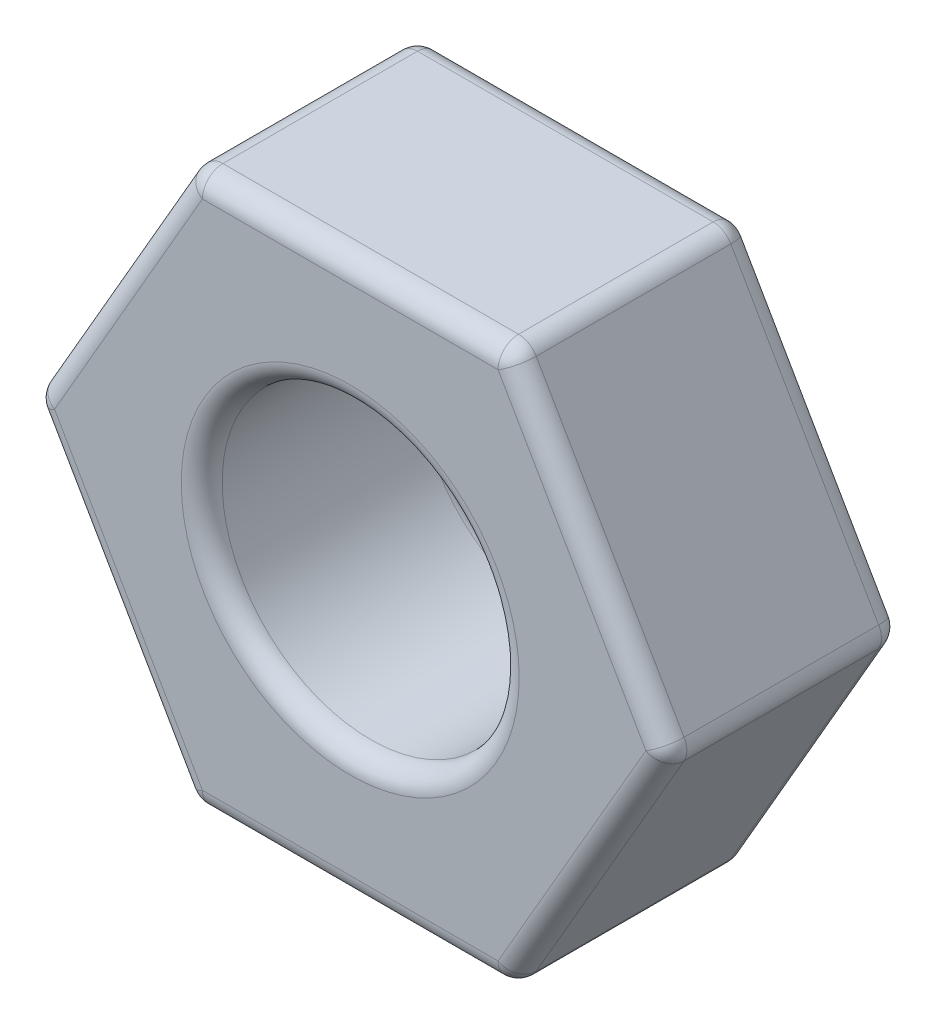
SolidWorks part; units mm, degrees
ref_plane "Plano frontal" through (0, 0, 0) normal (0, 0, 1) x (1, 0, 0)
ref_plane "Plano superior" through (0, 0, 0) normal (0, 1, 0) x (1, 0, 0)
ref_plane "Plano direito" through (0, 0, 0) normal (1, 0, 0) x (0, 0, -1)
sketch "Esboço1" plane through (0, 0, 0) normal (0, 0, 1) x (1, 0, 0)
  line L1 (-3.1177, 0) -> (-1.5588, -2.7)
  line L2 (-1.5588, -2.7) -> (1.5588, -2.7)
  line L3 (1.5588, -2.7) -> (3.1177, 0)
  line L4 (3.1177, 0) -> (1.5588, 2.7)
  line L5 (1.5588, 2.7) -> (-1.5588, 2.7)
  line L6 (-1.5588, 2.7) -> (-3.1177, 0)
  circle A0 centre (0, 0) radius 2.7 construction
  circle A1 centre (0, 0) radius 1.45
  dimension "D1" = 2.9
  dimension "D2" = 5.4
extrude "Ressalto-extrusão1" add sketch "Esboço1" along normal blind 2.3
fillet "Filete1" radius 0.2 20 edges at (-1.5588, -2.7, 1.15) (-1.5588, 2.7, 1.15) (-3.1177, 0, 1.15) (1.5588, 2.7, 1.15) (1.5588, -2.7, 1.15) (3.1177, 0, 1.15) (1.45, 0, 0) (-2.3383, -1.35, 0) (0, -2.7, 0) (2.3383, -1.35, 0) (2.3383, 1.35, 0) (0, 2.7, 0) (-2.3383, 1.35, 0) (1.45, 0, 2.3) (0, 2.7, 2.3) (2.3383, 1.35, 2.3) (2.3383, -1.35, 2.3) (0, -2.7, 2.3) (-2.3383, -1.35, 2.3) (-2.3383, 1.35, 2.3)
